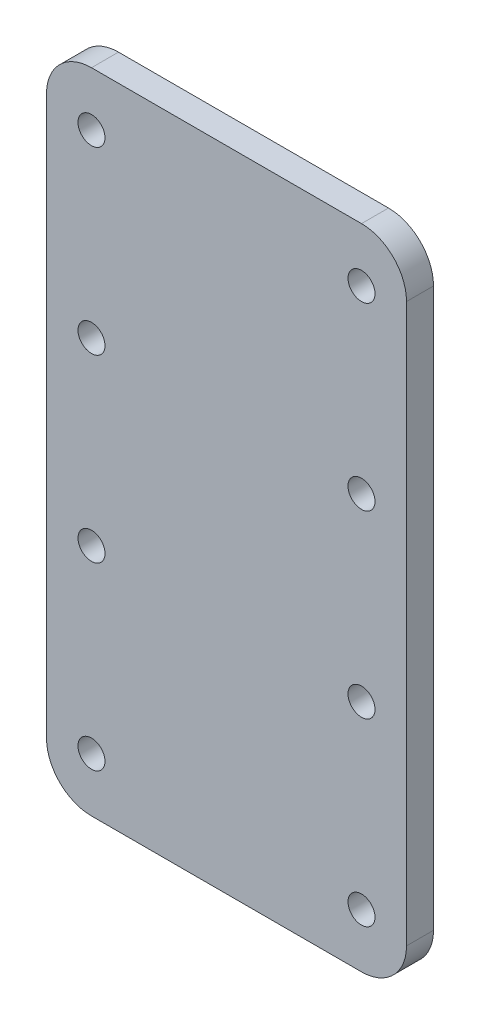
SolidWorks part; units mm, degrees
material "Thornel Mat VMA"
ref_plane "前视基准面" through (0, 0, 0) normal (0, 0, 1) x (1, 0, 0)
ref_plane "上视基准面" through (0, 0, 0) normal (0, 1, 0) x (1, 0, 0)
ref_plane "右视基准面" through (0, 0, 0) normal (1, 0, 0) x (0, 0, -1)
sketch "草图1" plane through (0, 0, 0) normal (0, 0, 1) x (1, 0, 0)
  line L1 (-20, -36) -> (20, -36)
  line L2 (-20, -36) -> (-20, 36)
  line L3 (-20, 36) -> (20, 36)
  line L4 (20, -36) -> (20, 36)
  line L5 (-20, -36) -> (20, 36) construction
  line L6 (-20, 36) -> (20, -36) construction
  point P0 (0, 0)
  dimension "D1" = 72
  dimension "D2" = 40
extrude "凸台-拉伸1" add sketch "草图1" along normal blind 3
sketch "草图2" plane through (0, 0, 3) normal (0, 0, 1) x (1, 0, 0)
  line L0 (-20, 0) -> (20, 0) construction
  line L1 (-20, 36) -> (-20, -36) construction
  line L2 (20, -36) -> (20, 36) construction
  line L3 (0, 0) -> (0, 20) construction
  line L5 (-15, 30) -> (15, 30) construction
  line L6 (-15, 30) -> (-15, 10) construction
  line L7 (-15, 10) -> (15, 10) construction
  line L8 (15, 30) -> (15, 10) construction
  line L9 (-15, 30) -> (15, 10) construction
  line L10 (-15, 10) -> (15, 30) construction
  circle A0 centre (-15, 30) radius 1.5
  circle A1 centre (-15, 10) radius 1.5
  circle A2 centre (15, 30) radius 1.5
  circle A3 centre (15, 10) radius 1.5
  circle A4 centre (-15, -10) radius 1.5
  circle A5 centre (15, -10) radius 1.5
  circle A6 centre (15, -30) radius 1.5
  circle A7 centre (-15, -30) radius 1.5
  dimension "D4" = 3
  dimension "D5" = 3
  dimension "D6" = 3
  dimension "D7" = 3
  dimension "D1" = 20
  dimension "D2" = 20
  dimension "D3" = 30
extrude "切除-拉伸1" cut sketch "草图2" against normal blind 3
fillet "圆角1" radius 5 4 edges at (-20, -36, 1.5) (20, -36, 1.5) (20, 36, 1.5) (-20, 36, 1.5)
